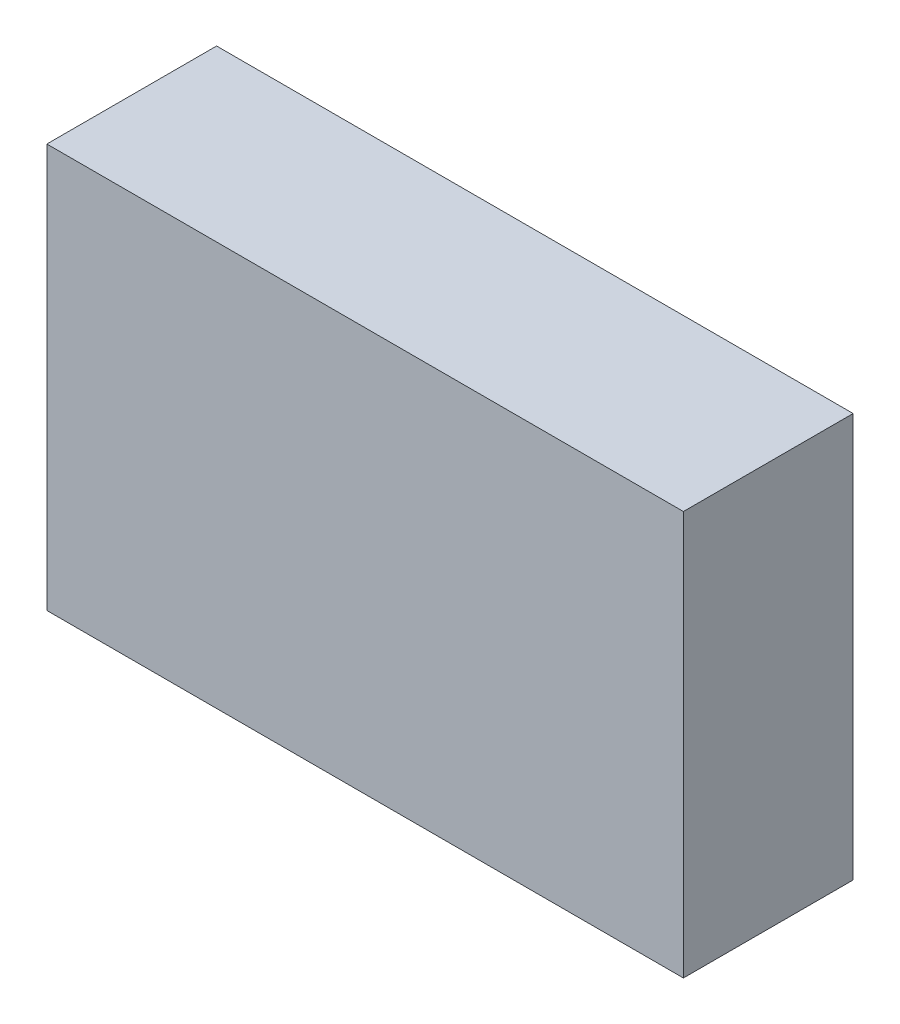
SolidWorks part; units mm, degrees
ref_plane "前视基准面" through (0, 0, 0) normal (0, 0, 1) x (1, 0, 0)
ref_plane "上视基准面" through (0, 0, 0) normal (0, 1, 0) x (1, 0, 0)
ref_plane "右视基准面" through (0, 0, 0) normal (1, 0, 0) x (0, 0, -1)
other "Configuration Table"
sketch "草图1" plane through (0, 0, 0) normal (0, 0, 1) x (1, 0, 0)
  line L1 (-37.5, 23.8) -> (37.5, 23.8)
  line L2 (-37.5, 23.8) -> (-37.5, -23.8)
  line L3 (-37.5, -23.8) -> (37.5, -23.8)
  line L4 (37.5, 23.8) -> (37.5, -23.8)
  line L5 (0, -23.8) -> (0, 23.8) construction
  line L6 (-37.5, 0) -> (37.5, 0) construction
  point P0 (0, 0)
  dimension "D1" = 75
  dimension "D2" = 47.6
extrude "凸台-拉伸1" add sketch "草图1" along normal blind 20
